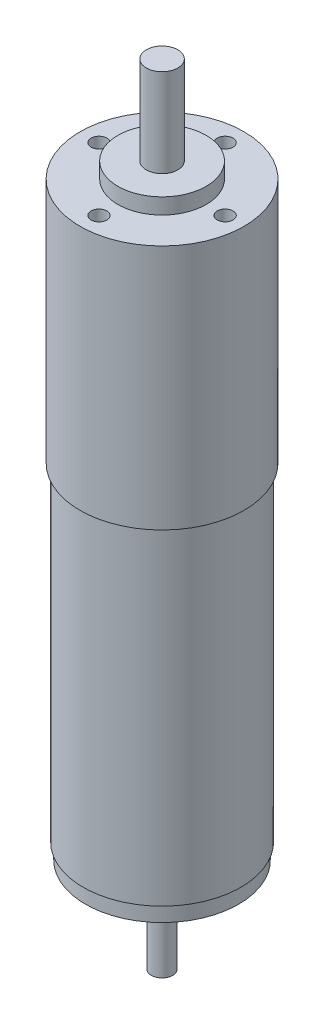
SolidWorks part; units mm, degrees
ref_plane "Face" through (0, 0, 0) normal (0, 0, 1) x (1, 0, 0)
ref_plane "Dessus" through (0, 0, 0) normal (0, 1, 0) x (1, 0, 0)
ref_plane "Droite" through (0, 0, 0) normal (1, 0, 0) x (0, 0, -1)
sketch "Esquisse1" plane through (0, 0, 0) normal (0, 0, 1) x (1, 0, 0)
  line L0 (0, 0) -> (0, 110) construction
  line L1 (0, 0) -> (12.15, 0)
  line L2 (12.15, 0) -> (12.15, 2.5)
  line L3 (12.15, 2.5) -> (12.5, 2.5)
  line L4 (12.5, 2.5) -> (12.5, 54.5)
  line L5 (12.5, 54.5) -> (13, 54.5)
  line L6 (13, 54.5) -> (13, 93.5)
  line L7 (13, 93.5) -> (7, 93.5)
  line L8 (7, 93.5) -> (7, 96)
  line L9 (7, 96) -> (2.5, 96)
  line L10 (2.5, 96) -> (2.5, 110)
  line L11 (2.5, 110) -> (0, 110)
  line L12 (0, 0) -> (0, 110)
  dimension "D1" = 5
  dimension "D2" = 25
  dimension "D3" = 26
  dimension "D4" = 54.5
  dimension "D5" = 14
  dimension "D6" = 14
  dimension "D7" = 2.5
  dimension "D8" = 39
  dimension "D9" = 24.3
  dimension "D10" = 2.5
revolve "Révolution1" add sketch "Esquisse1" angle 360 about L0
sketch "Esquisse2" plane through (0, 0, 0) normal (0, -1, 0) x (1, 0, 0)
  circle A0 centre (0, 0) radius 1.6928
extrude "Boss.-Extru.1" add sketch "Esquisse2" along normal blind 15
sketch "Esquisse3" plane through (0, 0, 0) normal (0, -1, 0) x (1, 0, 0)
  circle A0 centre (0, 0) radius 4
  dimension "D1" = 8
extrude "Boss.-Extru.2" add sketch "Esquisse3" along normal blind 2.5
sketch "Esquisse4" plane through (0, 93.5, 0) normal (0, 1, 0) x (1, 0, 0)
  line L0 (0, 0) -> (0, 13) construction
  line L1 (0, 0) -> (0, 10) construction
  circle A0 centre (0, 0) radius 13 construction
  circle A1 centre (0, 10) radius 1.25
  circle A2 centre (10, 0) radius 1.25
  circle A3 centre (0, -10) radius 1.25
  circle A4 centre (-10, 0) radius 1.25
  point P9 (-11.3902, 1.6177)
  dimension "D1" = 2.5
  dimension "D2" = 10
  dimension "D4" = 10
  dimension "D3" = 4
extrude "Enlèv. mat.-Extru.1" cut sketch "Esquisse4" against normal blind 5
